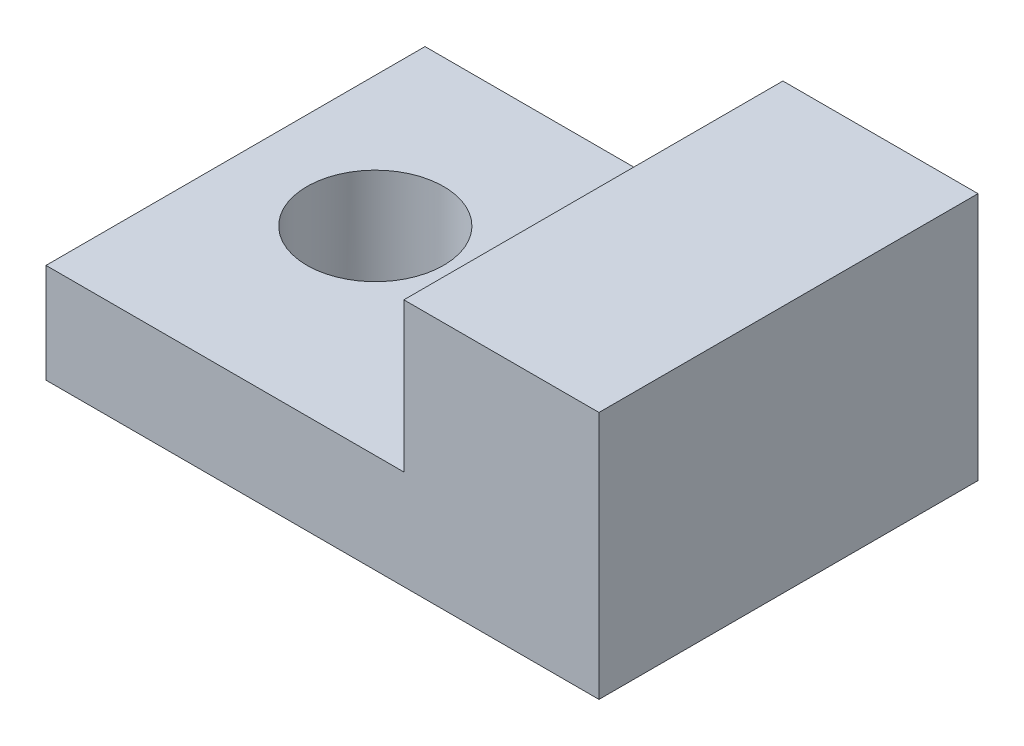
SolidWorks part; units mm, degrees
ref_plane "Front Plane" through (0, 0, 0) normal (0, 0, 1) x (1, 0, 0)
ref_plane "Top Plane" through (0, 0, 0) normal (0, 1, 0) x (1, 0, 0)
ref_plane "Right Plane" through (0, 0, 0) normal (1, 0, 0) x (0, 0, -1)
sketch "Sketch1" plane through (0, 0, 0) normal (0, 1, 0) x (1, 0, 0)
  line L1 (0, 0) -> (17.6609, 0)
  line L2 (0, 0) -> (0, 12.1047)
  line L3 (0, 12.1047) -> (17.6609, 12.1047)
  line L4 (17.6609, 0) -> (17.6609, 12.1047)
extrude "Boss-Extrude1" add sketch "Sketch1" along normal blind 7.9375 contours L3 L4 L1 L2
sketch "Sketch2" plane through (0, 0, 0) normal (0, 0, 1) x (1, 0, 0)
  line L1 (0, 7.9375) -> (11.43, 7.9375)
  line L2 (0, 7.9375) -> (0, 3.175)
  line L3 (0, 3.175) -> (11.43, 3.175)
  line L4 (11.43, 7.9375) -> (11.43, 3.175)
extrude "Cut-Extrude1" cut sketch "Sketch2" against normal blind 25.4
sketch "Sketch3" plane through (0, 3.175, 0) normal (0, 1, 0) x (1, 0, 0)
  line L0 (0, 6.35) -> (1.9844, 6.35)
  line L1 (0, 12.1047) -> (0, 0) construction
  line L2 (1.9844, 6.35) -> (4.1672, 6.35)
  circle A0 centre (4.1672, 6.35) radius 2.1828
extrude "Cut-Extrude2" cut sketch "Sketch3" against normal blind 25.4
